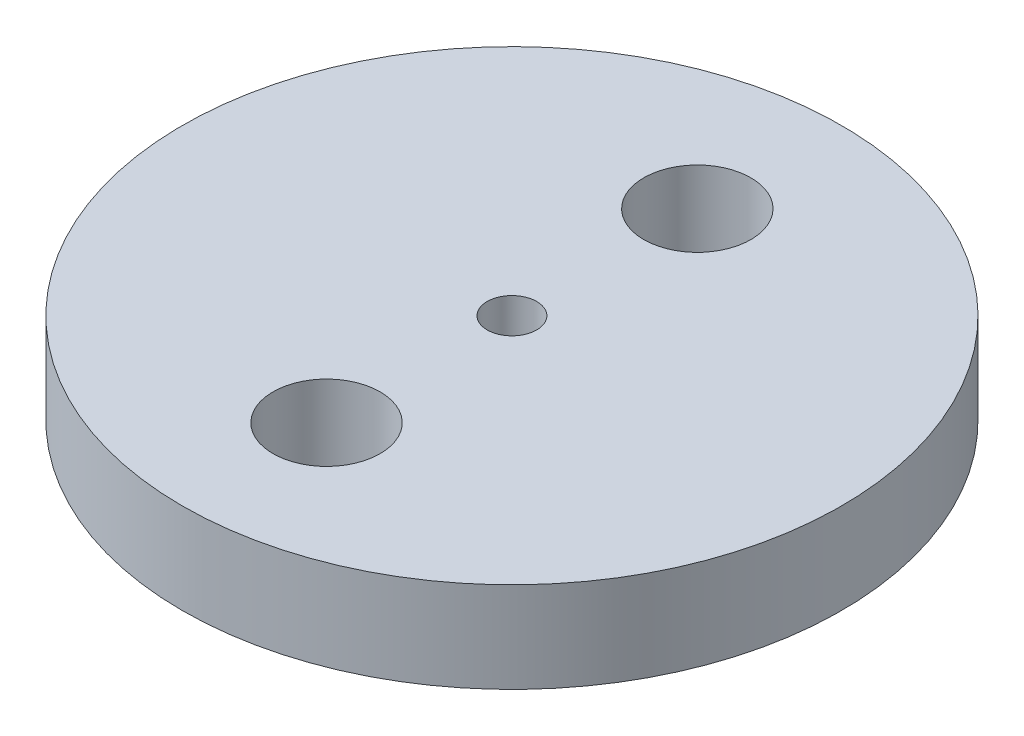
SolidWorks part; units mm, degrees
ref_plane "Front Plane" through (0, 0, 0) normal (0, 0, 1) x (1, 0, 0)
ref_plane "Top Plane" through (0, 0, 0) normal (0, 1, 0) x (1, 0, 0)
ref_plane "Right Plane" through (0, 0, 0) normal (1, 0, 0) x (0, 0, -1)
sketch "Sketch1" plane through (0, 0, 0) normal (0, 1, 0) x (1, 0, 0)
  circle A0 centre (0, 0) radius 8
  dimension "D1" = 16
extrude "Boss-Extrude1" add sketch "Sketch1" along normal blind 2.2
sketch "Sketch2" plane through (0, 2.2, 0) normal (0, 1, 0) x (1, 0, 0)
  line L0 (0, -16.0698) -> (0, 16.0698) construction
  line L1 (-27.9531, 0) -> (27.9531, 0) construction
  circle A2 centre (0, 4.5) radius 1.3
  circle A12 centre (0, -4.5) radius 1.3
  point P3 (0, 0)
  point P9 (0, 0)
  dimension "D1" = 2.6
  dimension "D2" = 4.5
extrude "Cut-Extrude1" cut sketch "Sketch2" against normal blind 2.2
sketch "Sketch3" plane through (0, 0, 0) normal (0, -1, 0) x (1, 0, 0)
  circle A0 centre (0, 0) radius 3
  circle A1 centre (0, 0) radius 2.45
  dimension "D1" = 6
  dimension "D2" = 4.9
extrude "Boss-Extrude2" add sketch "Sketch3" along normal blind 2.2
sketch "Sketch8" plane through (0, 0, 0) normal (0, -1, 0) x (1, 0, 0)
  circle A0 centre (0, 0) radius 0.6
  dimension "D1" = 1.2
extrude "Cut-Extrude7" cut sketch "Sketch8" against normal up to surface (2.2 mm away) up to face at (0, 2.2, 3.2)
